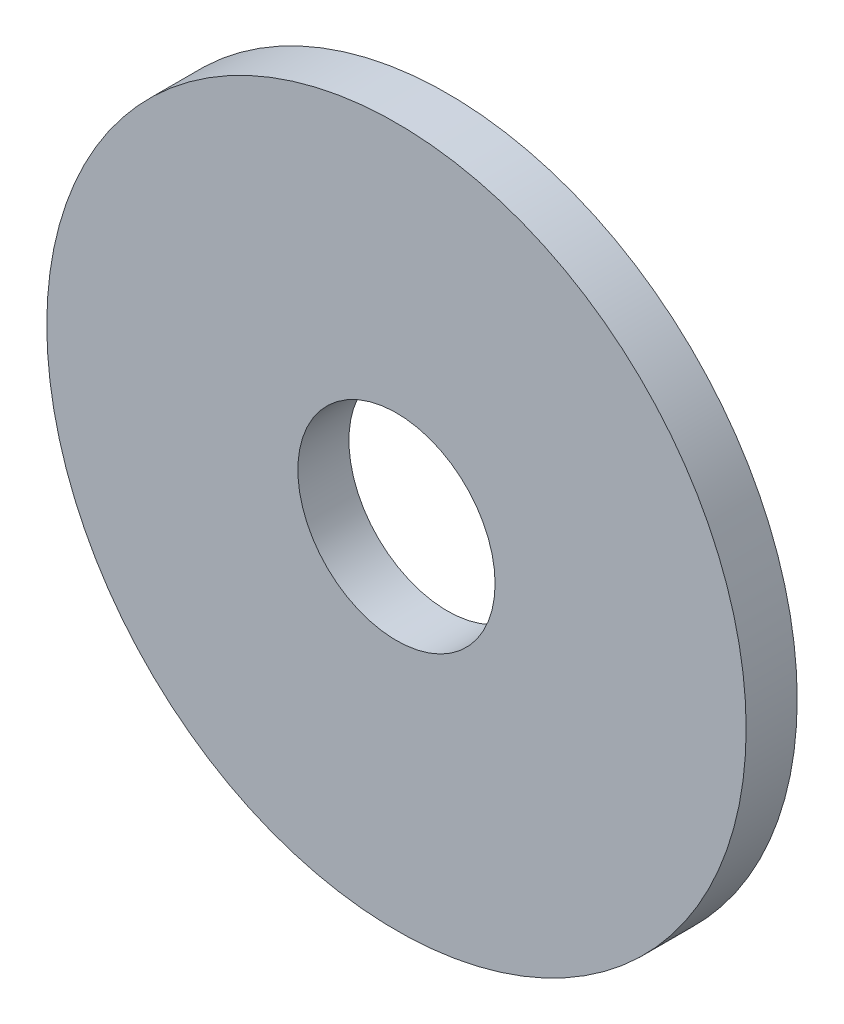
SolidWorks part; units mm, degrees
other "Imported1"
ref_plane "Front Plane" through (0, 0, 0) normal (0, 0, 1) x (1, 0, 0)
ref_plane "Top Plane" through (0, 0, 0) normal (0, 1, 0) x (1, 0, 0)
ref_plane "Right Plane" through (0, 0, 0) normal (1, 0, 0) x (0, 0, -1)
sketch "Sketch1" plane through (0, 0, 0) normal (0, 0, 1) x (1, 0, 0)
  line L0 (-6.35, 0) -> (6.35, 0) construction
  line L1 (-1.7907, 0) -> (1.7907, 0) construction
  circle A0 centre (0, 0) radius 1.7907 construction
  circle A1 centre (0, 0) radius 6.35 construction
  point P8 (0, 0)
  point P9 (0, 6.35)
  point P10 (0, -1.7907)
  point P11 (1.7907, 0)
  dimension "ID" = 3.5814
  dimension "OD" = 12.7
sketch "Sketch2" plane through (0, 0, 0) normal (1, 0, 0) x (0, 0, -1)
  line L0 (-0.4635, 6.35) -> (0.4636, 6.35) construction
  point P2 (0, 6.35)
  dimension "Thickness Range" = 0.9271
sketch "Sketch3" plane through (0, 0, 0) normal (0, 0, 1) x (1, 0, 0)
  circle A0 centre (0, 0) radius 1.7907
  circle A1 centre (0, 0) radius 6.35
extrude "Boss-Extrude1" add sketch "Sketch3" along normal up to vertex (0.4636 mm away) and the other way up to vertex (0.4636 mm away) up to point (0, 6.35, 0.4635) other way up to point (0, 6.35, -0.4636)
